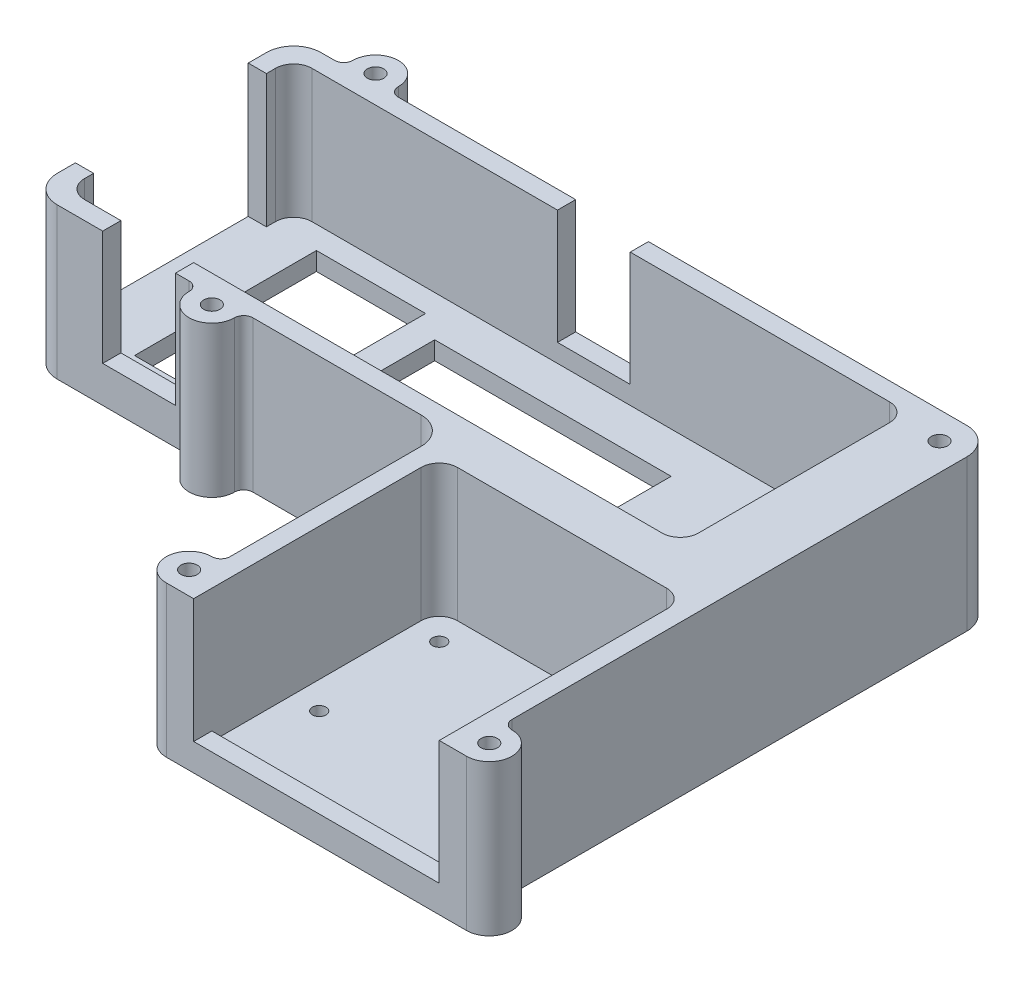
SolidWorks part; units mm, degrees
ref_plane "Alzado" through (0, 0, 0) normal (0, 0, 1) x (1, 0, 0)
ref_plane "Planta" through (0, 0, 0) normal (0, 1, 0) x (1, 0, 0)
ref_plane "Vista lateral" through (0, 0, 0) normal (1, 0, 0) x (0, 0, -1)
sketch "Croquis1" plane through (0, 0, 0) normal (0, 1, 0) x (1, 0, 0)
  line L5 (31, 29) -> (31, -30)
  line L6 (-46, 29) -> (31, 29)
  line L7 (-46, 0) -> (-46, 29)
  line L8 (0, 0) -> (-46, 0)
  line L9 (0, -30) -> (0, 0)
  line L10 (31, -30) -> (0, -30)
  line L12 (-39, 24.5) -> (-27, 24.5)
  line L13 (-39, 24.5) -> (-39, 4.5)
  line L14 (-39, 4.5) -> (-27, 4.5)
  line L15 (-27, 24.5) -> (-27, 4.5)
  line L16 (-24, 22.5) -> (2, 22.5)
  line L17 (-24, 22.5) -> (-24, 6.5)
  line L18 (-24, 6.5) -> (2, 6.5)
  line L19 (2, 22.5) -> (2, 6.5)
  point P1 (-46, 14.5)
  point P2 (-39, 14.5)
  point P17 (-24, 14.5)
  point P18 (-27, 14.5)
  dimension "D1" = 59
  dimension "D2" = 77
  dimension "D3" = 29
  dimension "D4" = 31
  dimension "D5" = 19
  dimension "D6" = 12
  dimension "D7" = 20
  dimension "D8" = 22
  dimension "D9" = 26
  dimension "D10" = 16
extrude "Saliente-Extruir1" add sketch "Croquis1" along normal blind 2
sketch "Croquis2" plane through (0, 2, 0) normal (0, 1, 0) x (1, 0, 0)
  line L1 (0, -30) -> (31, -30)
  line L2 (31, -30) -> (31, 29)
  line L3 (31, -30) -> (31, 29) construction
  line L4 (31, 29) -> (-46, 29)
  line L5 (31, 29) -> (-46, 29) construction
  line L7 (-46, 0) -> (0, 0)
  line L10 (29, -28) -> (29, -3)
  line L15 (23.5, 2) -> (23.5, 27)
  line L16 (29, 27) -> (-44, 27) construction
  line L17 (29, -28) -> (29, 27) construction
  line L18 (-44, 27) -> (-44, 2) construction
  line L19 (-44, 2) -> (2, 2) construction
  line L20 (23.5, 27) -> (-44, 27)
  line L22 (-46, 5) -> (-46, 0)
  line L23 (-46, 29) -> (-46, 0) construction
  line L24 (2, 2) -> (2, -28) construction
  line L25 (0, 0) -> (0, -30) construction
  line L26 (2, -28) -> (29, -28) construction
  line L27 (29, -28) -> (2, -28)
  line L28 (0, 0) -> (0, -30) construction
  line L31 (-44, 2) -> (23.5, 2)
  line L33 (2, -3) -> (29, -3)
  line L34 (-46, 29) -> (-46, 24)
  line L35 (-46, 29) -> (-46, 0) construction
  line L36 (-46, 24) -> (-44, 24)
  line L37 (-44, 24) -> (-44, 27)
  line L39 (-46, 5) -> (-44, 5)
  line L40 (-44, 5) -> (-44, 2)
  line L43 (0, 0) -> (0, -30)
  line L45 (2, -3) -> (2, -28)
  point P20 (-23, 0)
  point P22 (0, 0)
  point P27 (0, 0)
  dimension "D1" = 2
  dimension "D2" = 7.5
  dimension "D3" = 2
  dimension "D4" = 2
  dimension "D5" = 5
  dimension "D6" = 2
  dimension "D7" = 3
  dimension "D8" = 25
  dimension "D9" = 25
  dimension "D10" = 67.5
  dimension "D11" = 2
extrude "Saliente-Extruir2" add sketch "Croquis2" along normal blind 14.6
sketch "Croquis3" plane through (0, 0, 30) normal (0, 0, 1) x (1, 0, 0)
  line L1 (2, 3) -> (29, 3)
  line L2 (2, 3) -> (2, 16.6)
  line L3 (2, 16.6) -> (29, 16.6)
  line L4 (29, 3) -> (29, 16.6)
  line L5 (29, 16.6) -> (29, 2) construction
  line L6 (29, 2) -> (2, 2) construction
  line L7 (0, 16.6) -> (31, 16.6) construction
  line L9 (2, 16.6) -> (2, 2) construction
  point P12 (0, 0)
  point P13 (0, 0)
  dimension "D1" = 1
extrude "Cortar-Extruir1" cut sketch "Croquis3" against normal up to surface (2 mm away) up to face at (15.5, 9.3, 28)
fillet "Redondeo1" radius 3 4 edges at (31, 8.3, -29) (0, 8.3, 0) (-46, 8.3, 0) (-46, 8.3, -29)
fillet "Redondeo2" radius 2 6 edges at (23.5, 9.3, -2) (23.5, 9.3, -27) (29, 9.3, 3) (-44, 9.3, -2) (-44, 9.3, -27) (2, 9.3, 3)
sketch "Croquis4" plane through (0, 0, 0) normal (0, 0, 1) x (1, 0, 0)
  line L0 (-43, 16.6) -> (-3, 16.6) construction
  line L1 (-38, 16.6) -> (-30, 16.6)
  line L2 (-38, 16.6) -> (-38, 4)
  line L3 (-38, 4) -> (-30, 4)
  line L4 (-30, 16.6) -> (-30, 4)
  line L5 (21.5, 2) -> (-42, 2) construction
  line L6 (-46, 0) -> (-46, 16.6) construction
  dimension "D1" = 2
  dimension "D2" = 16
  dimension "D3" = 8
extrude "Cortar-Extruir2" cut sketch "Croquis4" against normal up to surface (2 mm away) up to face at (-10.25, 9.3, -2)
sketch "Croquis5" plane through (0, 0, -29) normal (0, 0, -1) x (-1, 0, 0)
  line L0 (-28, 16.6) -> (43, 16.6) construction
  line L1 (7, 16.6) -> (15, 16.6)
  line L2 (7, 16.6) -> (7, 4)
  line L3 (7, 4) -> (15, 4)
  line L4 (15, 16.6) -> (15, 4)
  line L5 (46, 16.6) -> (46, 0) construction
  line L7 (42, 2) -> (-21.5, 2) construction
  dimension "D1" = 8
  dimension "D2" = 39
  dimension "D3" = 2
extrude "Cortar-Extruir3" cut sketch "Croquis5" against normal up to surface (2 mm away) up to face at (-10.25, 9.3, -27)
sketch "Croquis6" plane through (0, 2, 0) normal (0, 1, 0) x (1, 0, 0)
  line L0 (4, -3) -> (27, -3) construction
  line L1 (5, -6) -> (26, -6) construction
  line L2 (5, -6) -> (5, -19.2) construction
  line L3 (5, -19.2) -> (26, -19.2) construction
  line L4 (26, -6) -> (26, -19.2) construction
  line L5 (29, -5) -> (29, -28) construction
  circle A1 centre (26, -6) radius 0.75
  circle A2 centre (5, -6) radius 0.75
  circle A3 centre (5, -19.2) radius 0.75
  circle A4 centre (26, -19.2) radius 0.75
  dimension "D1" = 1.5
  dimension "D2" = 3
  dimension "D3" = 24
  dimension "D4" = 21
  dimension "D5" = 13.2
extrude "Cortar-Extruir4" cut sketch "Croquis6" against normal up to surface (2 mm away) up to face at (-9.1, 0, -5.1243)
sketch "Croquis7" plane through (0, 16.6, 0) normal (0, 1, 0) x (1, 0, 0)
  line L0 (31, -30) -> (31, 26) construction
  line L1 (-15, 29) -> (-43, 29) construction
  line L3 (29, -30) -> (29, -5) construction
  line L5 (31, -30) -> (31, -24)
  line L10 (-1, -30) -> (0, -30)
  line L11 (15.5, -30) -> (15.5, -28) construction
  line L12 (2, -30) -> (29, -30) construction
  line L16 (2, -28) -> (29, -28) construction
  line L17 (-30, 2) -> (-30, 0) construction
  line L21 (-34.5, 29) -> (-41.5, 29)
  line L24 (-46, 26) -> (-46, 24) construction
  line L25 (-42, 27) -> (21.5, 27) construction
  line L26 (32, -30) -> (31, -30)
  line L27 (29, -30) -> (31, -30) construction
  line L31 (0, -30) -> (0, -24)
  line L32 (-21.5, 0) -> (-28.5, 0)
  line L33 (-30, 0) -> (-3, 0) construction
  line L34 (21.5, 2) -> (-42, 2) construction
  circle A2 centre (32, -27.5) radius 0.9
  arc A3 (32, -30) -> (32, -25) centre (32, -27.5) ccw
  arc A19 (-35.5, 30) -> (-40.5, 30) centre (-38, 30) ccw
  circle A21 centre (-38, 30) radius 0.9
  arc A26 (32, -25) -> (31, -24) centre (32, -24) cw
  arc A27 (-1, -25) -> (0, -24) centre (-1, -24) ccw
  arc A28 (-1, -30) -> (-1, -25) centre (-1, -27.5) cw
  circle A29 centre (-1, -27.5) radius 0.9
  arc A30 (-40.5, 30) -> (-41.5, 29) centre (-41.5, 30) cw
  arc A31 (-35.5, 30) -> (-34.5, 29) centre (-34.5, 30) ccw
  arc A36 (-27.5, -1) -> (-28.5, 0) centre (-28.5, -1) ccw
  arc A37 (-22.5, -1) -> (-21.5, 0) centre (-21.5, -1) cw
  circle A38 centre (-25, -1) radius 0.9
  arc A39 (-22.5, -1) -> (-27.5, -1) centre (-25, -1) cw
  dimension "D1" = 2.5
  dimension "D2" = 8
  dimension "D3" = 1.8
  dimension "D4" = 5
  dimension "D5" = 3
  dimension "D6" = 1.8
  dimension "D7" = 2.5
  dimension "D9" = 3
  dimension "D8" = 1.8
  dimension "D10" = 5
  dimension "D11" = 3
extrude "Saliente-Extruir3" add sketch "Croquis7" against normal up to surface (16.6 mm away) up to face at (26, 0, 18.45)
sketch "Croquis8" plane through (0, 16.6, 0) normal (0, 1, 0) x (1, 0, 0)
  line L0 (31, -24) -> (31, 26) construction
  line L1 (28, 29) -> (-7, 29) construction
  circle A0 centre (28, 26) radius 0.9
  dimension "D1" = 1.8
  dimension "D2" = 3
  dimension "D3" = 3
extrude "Cortar-Extruir5" cut sketch "Croquis8" against normal blind 6
